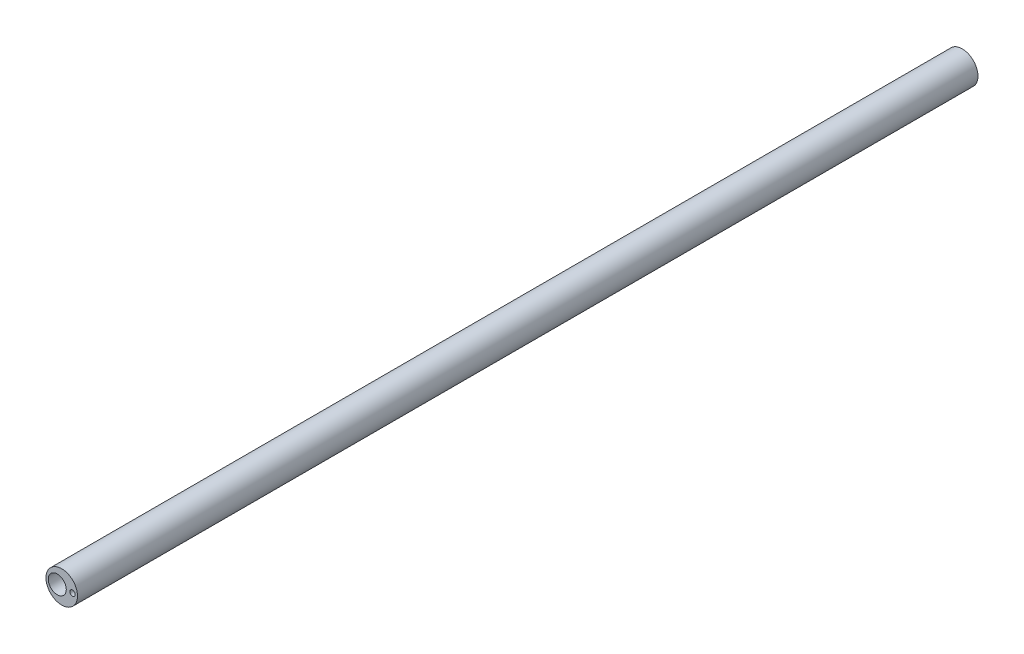
SolidWorks part; units mm, degrees
ref_plane "Front Plane" through (0, 0, 0) normal (0, 0, 1) x (1, 0, 0)
ref_plane "Top Plane" through (0, 0, 0) normal (0, 1, 0) x (1, 0, 0)
ref_plane "Right Plane" through (0, 0, 0) normal (1, 0, 0) x (0, 0, -1)
sketch "Sketch1" plane through (0, 0, 0) normal (0, 0, 1) x (1, 0, 0)
  line L0 (-1.75, 0) -> (1.75, 0) construction
  line L1 (1.496, 0) -> (1.75, 0) construction
  line L2 (-1.496, 0) -> (-1.75, 0) construction
  line L3 (0.504, 0) -> (0.896, 0) construction
  circle A0 centre (0, 0) radius 1.75
  circle A1 centre (-0.496, 0) radius 1
  circle A2 centre (1.196, 0) radius 0.3
  dimension "D1" = 3.5
  dimension "D2" = 2
  dimension "D3" = 0.6
  dimension "D6" = 0.392
  dimension "D4" = 0.254
  dimension "D5" = 0.254
extrude "Boss-Extrude1" add sketch "Sketch1" along normal blind 100 contours A0 A2 A1
